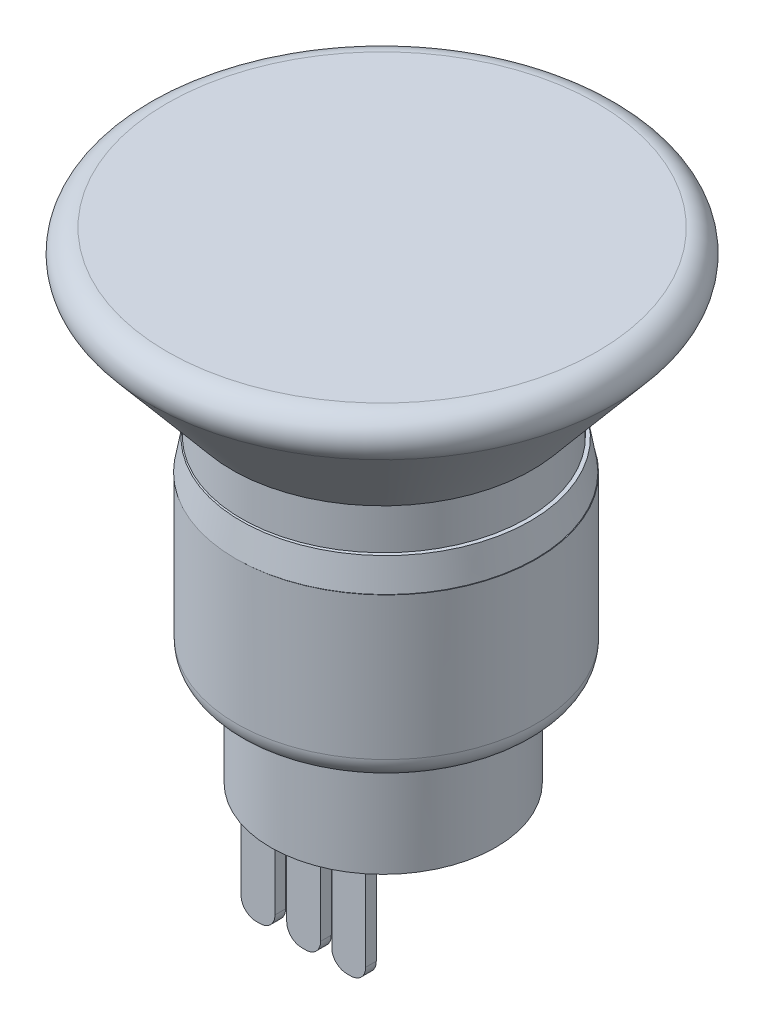
SolidWorks part; units mm, degrees
ref_plane "Plan de face" through (0, 0, 0) normal (0, 0, 1) x (1, 0, 0)
ref_plane "Plan de dessus" through (0, 0, 0) normal (0, 1, 0) x (1, 0, 0)
ref_plane "Plan de droite" through (0, 0, 0) normal (1, 0, 0) x (0, 0, -1)
sketch "Esquisse1" plane through (-11.1983, 0, 0) normal (0, 0, 1) x (1, 0, 0)
  line L0 (0, -8.4139) -> (0, -19.4139)
  dimension "D1" = 11
revolve "Révol.-Mince1" add sketch "Esquisse1" angle 360 about L0 wall 10
sketch "Esquisse4" plane through (0, -8.4139, 0) normal (0, 1, 0) x (1, 0, 0)
  circle A0 centre (-11.2453, 0) radius 10
  dimension "D1" = 20
extrude "Boss.-Extru.1" add sketch "Esquisse4" along normal blind 2 draft 10
sketch "Esquisse5" plane through (0, -6.4139, 0) normal (0, 1, 0) x (1, 0, 0)
  circle A0 centre (-11.3639, 0) radius 9.5
  point P2 (-11.3639, 0)
  dimension "D1" = 19
extrude "Boss.-Extru.2" add sketch "Esquisse5" along normal blind 3
sketch "Esquisse6" plane through (0, -3.4139, 0) normal (0, 1, 0) x (1, 0, 0)
  circle A0 centre (-11.4826, 0) radius 10
  dimension "D1" = 20
extrude "Boss.-Extru.3" add sketch "Esquisse6" along normal blind 9 draft 40 draft outward yes
fillet "Congé2" radius 1.5 2 edges at (-29.0345, 5.5861, 0) (-21.1983, -19.4139, 0)
sketch "Esquisse7" plane through (0, -19.4139, 0) normal (0, -1, 0) x (-1, 0, 0)
  circle A0 centre (11.412, 0) radius 7.5
  dimension "D1" = 15
extrude "Boss.-Extru.4" add sketch "Esquisse7" along normal blind 7
sketch "Esquisse8" plane through (0, -26.4139, 0) normal (0, -1, 0) x (-1, 0, 0)
  line L0 (11.4826, -15.4842) -> (11.4826, 15.4842) construction
  line L1 (15.6345, -5.2492) -> (13.3746, -5.2492)
  line L2 (15.6345, -5.2492) -> (15.6345, -4.543)
  line L3 (15.6345, -4.543) -> (13.3746, -4.543)
  line L4 (13.3746, -5.2492) -> (13.3746, -4.543)
  line L5 (7.3307, -5.2492) -> (7.3307, -4.543)
  line L6 (7.3307, -4.543) -> (9.5906, -4.543)
  line L7 (9.5906, -5.2492) -> (9.5906, -4.543)
  line L8 (7.3307, -5.2492) -> (9.5906, -5.2492)
  line L13 (10.3307, -5.2492) -> (10.3307, -4.543)
  line L14 (10.3307, -4.543) -> (12.5906, -4.543)
  line L15 (12.5906, -5.2492) -> (12.5906, -4.543)
  line L16 (10.3307, -5.2492) -> (12.5906, -5.2492)
  circle A0 centre (11.4826, 0) radius 15.4842 construction
  dimension "D1" = 2
extrude "Boss.-Extru.5" add sketch "Esquisse8" along normal blind 7
fillet "Congé3" radius 1 6 edges at (-10.3307, -33.4139, 4.8961) (-12.5906, -33.4139, 4.8961) (-15.6345, -33.4139, 4.8961) (-13.3746, -33.4139, 4.8961) (-9.5906, -33.4139, 4.8961) (-7.3307, -33.4139, 4.8961)
